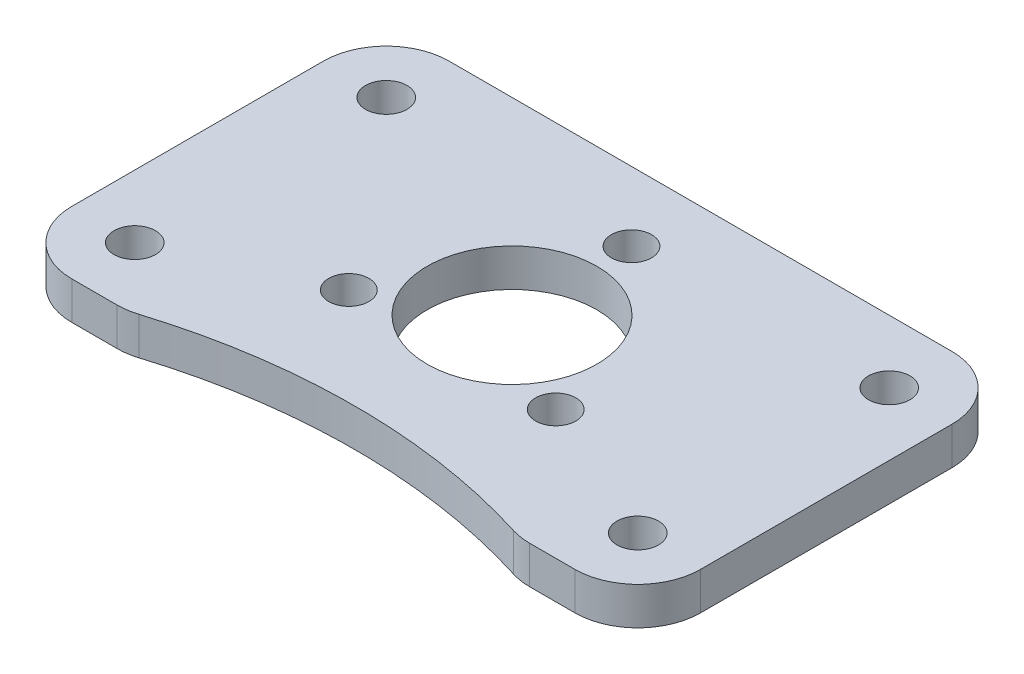
SolidWorks part; units mm, degrees
material "5052-H34"
ref_plane "正面" through (0, 0, 0) normal (0, 0, 1) x (1, 0, 0)
ref_plane "平面" through (0, 0, 0) normal (0, 1, 0) x (1, 0, 0)
ref_plane "右側面" through (0, 0, 0) normal (1, 0, 0) x (0, 0, -1)
sketch "ｽｹｯﾁ1" plane through (0, 0, 0) normal (0, 1, 0) x (1, 0, 0)
  line L0 (25, 0) -> (25, 30) construction
  line L1 (0, 0) -> (9.3875, 0)
  line L2 (0, 0) -> (0, 30)
  line L3 (0, 30) -> (50, 30)
  line L4 (50, 0) -> (50, 30)
  line L5 (25, 15) -> (50, 15) construction
  line L6 (25, 15) -> (25, -47.5) construction
  line L11 (25, 0) -> (40.6125, 0) construction
  line L13 (40.6125, 0) -> (50, 0)
  line L14 (9.3875, 0) -> (25, 0) construction
  circle A0 centre (45, 5) radius 1.65
  circle A1 centre (5, 5) radius 1.65
  circle A2 centre (5, 25) radius 1.65
  circle A3 centre (45, 25) radius 1.65
  circle A4 centre (25, 15) radius 6.75
  circle A9 centre (25, 24.5) radius 1.6
  circle A10 centre (33.2272, 10.25) radius 1.6
  circle A11 centre (16.7728, 10.25) radius 1.6
  arc A12 (40.6125, 0) -> (9.3875, 0) centre (25, -47.5) ccw
  arc A13 (9.3875, 0) -> (40.6125, 0) centre (25, -47.5) ccw construction
  point P26 (25, 15)
  point P31 (35, 22.5)
  dimension "D5" = 3.3
  dimension "D6" = 13.5
  dimension "D8" = 3.2
  dimension "D11" = 100
  dimension "D1" = 50
  dimension "D2" = 30
  dimension "D3" = 40
  dimension "D4" = 20
  dimension "D7" = 9.5
  dimension "D10" = 62.5
  dimension "D9" = 3
extrude "ﾎﾞｽ - 押し出し1" add sketch "ｽｹｯﾁ1" along normal blind 3
fillet "ﾌｨﾚｯﾄ1" radius 5 6 edges at (0, 1.5, -30) (50, 1.5, -30) (0, 1.5, 0) (50, 1.5, 0) (40.6125, 1.5, 0) (9.3875, 1.5, 0)
